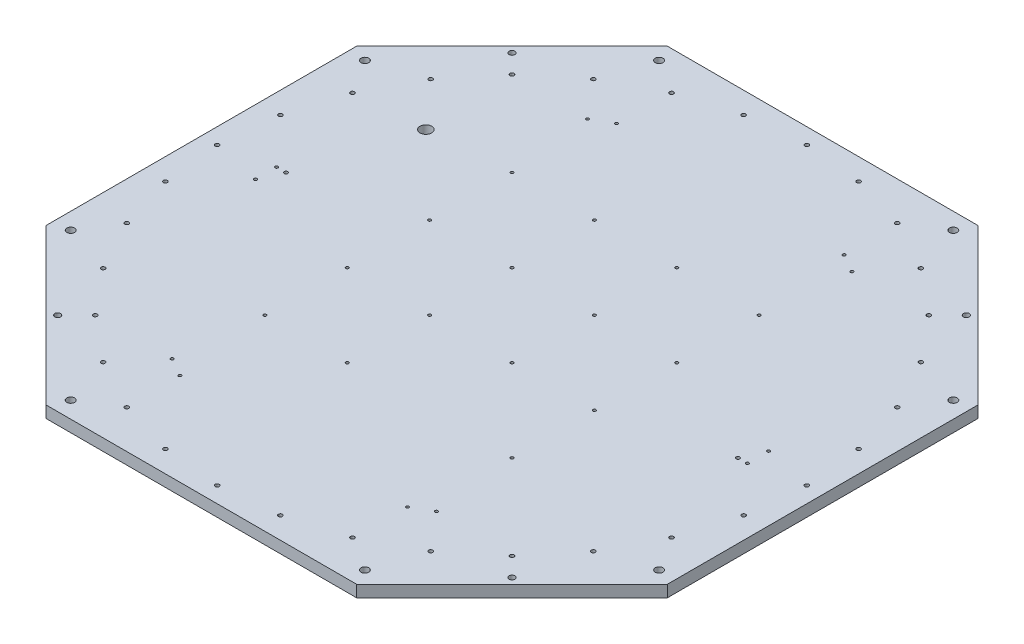
SolidWorks part; units mm, degrees
material "AISI 304"
ref_plane "Front" through (0, 0, 0) normal (0, 0, 1) x (1, 0, 0)
ref_plane "Top" through (0, 0, 0) normal (0, 1, 0) x (1, 0, 0)
ref_plane "Right" through (0, 0, 0) normal (1, 0, 0) x (0, 0, -1)
sketch "Sketch1" plane through (0, 0, 0) normal (0, 1, 0) x (1, 0, 0)
  line L0 (-131.9798, 264) -> (131.9798, 264)
  line L1 (131.9798, 264) -> (264, 131.9798)
  line L2 (264, 131.9798) -> (264, -131.9798)
  line L3 (264, 0) -> (0, 0) construction
  line L4 (0, 0) -> (0, 264) construction
  line L5 (131.9798, -264) -> (264, -131.9798)
  line L6 (-131.9798, -264) -> (131.9798, -264)
  line L7 (-131.9798, -264) -> (-264, -131.9798)
  line L8 (-264, 131.9798) -> (-264, -131.9798)
  line L9 (-131.9798, 264) -> (-264, 131.9798)
  point P12 (0, -264)
  point P21 (0, 0)
  dimension "D1" = 528
  dimension "D2" = 280
extrude "Boss-Extrude1" add sketch "Sketch1" along normal mid plane 10
hole_wizard "M3 Clearance Hole1" positions "Sketch2" profile "Sketch3" hole size "M3" standard "ANSI Metric" end condition up to next
sketch "Sketch2" plane through (0, 5, 0) normal (0, 1, 0) x (1, 0, 0)
  line L0 (-250.5, 0) -> (250.5, 0) construction
  point P0 (250.5, 0)
  point P6 (245.6867, -48.8701)
  point P7 (231.4318, -95.8622)
  point P8 (208.2831, -139.1703)
  point P9 (177.1302, -177.1302)
  point P10 (139.1703, -208.2831)
  point P11 (95.8622, -231.4318)
  point P12 (48.8701, -245.6867)
  point P13 (0, -250.5)
  point P14 (-48.8701, -245.6867)
  point P15 (-95.8622, -231.4318)
  point P16 (-139.1703, -208.2831)
  point P17 (-177.1302, -177.1302)
  point P18 (-208.2831, -139.1703)
  point P19 (-231.4318, -95.8622)
  point P20 (-245.6867, -48.8701)
  point P21 (-250.5, 0)
  point P22 (-245.6867, 48.8701)
  point P23 (-231.4318, 95.8622)
  point P24 (-208.2831, 139.1703)
  point P25 (-177.1302, 177.1302)
  point P26 (-139.1703, 208.2831)
  point P27 (-95.8622, 231.4318)
  point P28 (-48.8701, 245.6867)
  point P29 (0, 250.5)
  point P30 (48.8701, 245.6867)
  point P31 (95.8622, 231.4318)
  point P32 (139.1703, 208.2831)
  point P33 (177.1302, 177.1302)
  point P34 (208.2831, 139.1703)
  point P35 (231.4318, 95.8622)
  point P36 (245.6867, 48.8701)
  dimension "D2" = 501
  dimension "D1" = 32
sketch "Sketch3" plane through (250.5, 5, 0) normal (1, 0, 0) x (0, 0, 1)
  line L0 (0, 0) -> (0, 10)
  line L1 (0, 10) -> (1.7, 10)
  line L2 (1.7, 10) -> (1.7, 0)
  line L5 (1.7, 0) -> (0, 0)
  line L11 (0, -6.35) -> (0, 107.95) construction
  dimension "Thru Hole Dia." = 3.4
  dimension "Thru Hole Depth" = 10
hole_wizard "M3x0.5 Tapped Hole1" positions "Sketch10" profile "Sketch11" tap size "M3x0.5" standard "ANSI Metric"
sketch "Sketch10" plane through (0, 5, 0) normal (0, 1, 0) x (1, 0, 0)
  line L0 (209, 9) -> (209, 0) construction
  line L1 (209, 0) -> (209, -9) construction
  line L6 (0, 0) -> (209, 0) construction
  line L7 (-209, 9) -> (-209, -9) construction
  line L9 (-209, 0) -> (0, 0) construction
  point P0 (209, 9)
  point P2 (209, -9)
  point P39 (112.2942, -176.4993)
  point P40 (96.7058, -185.4993)
  point P41 (-96.7058, -185.4993)
  point P42 (-112.2942, -176.4993)
  point P43 (-209, -9)
  point P44 (-209, 9)
  point P45 (-112.2942, 176.4993)
  point P46 (-96.7058, 185.4993)
  point P47 (96.7058, 185.4993)
  point P48 (112.2942, 176.4993)
  dimension "D1" = 18
  dimension "D2" = 6
  dimension "D3" = 209
sketch "Sketch11" plane through (209, 5, -9) normal (1, 0, 0) x (0, 0, 1)
  line L0 (0, 0) -> (0, 8.2511)
  line L1 (0, 8.2511) -> (1.25, 7.5)
  line L2 (1.25, 7.5) -> (1.25, 0)
  line L5 (1.25, 0) -> (0, 0)
  line L10 (0, 8.2511) -> (-1.25, 7.5) construction
  line L11 (0, -6.35) -> (0, 107.95) construction
  dimension "Tap Drill Dia." = 2.5
  dimension "Tap Drill Depth" = 7.5
  dimension "Drill Angle" = 118
cosmetic thread "Hole Thread1" parameters "D1"=6, "D2"=3
cosmetic thread "Hole Thread2" parameters "D1"=6, "D2"=3
cosmetic thread "Hole Thread3" parameters "D1"=6, "D2"=3
cosmetic thread "Hole Thread4" parameters "D1"=6, "D2"=3
cosmetic thread "Hole Thread5" parameters "D1"=6, "D2"=3
cosmetic thread "Hole Thread6" parameters "D1"=6, "D2"=3
cosmetic thread "Hole Thread7" parameters "D1"=6, "D2"=3
cosmetic thread "Hole Thread8" parameters "D1"=6, "D2"=3
cosmetic thread "Hole Thread9" parameters "D1"=6, "D2"=3
cosmetic thread "Hole Thread10" parameters "D1"=6, "D2"=3
cosmetic thread "Hole Thread11" parameters "D1"=6, "D2"=3
cosmetic thread "Hole Thread12" parameters "D1"=6, "D2"=3
hole_wizard "Ø3.0mm Dowel Hole1" positions "Sketch12" profile "Sketch13" hole size "Ø3.0" standard "ANSI Metric"
sketch "Sketch12" plane through (0, 5, 0) normal (0, 1, 0) x (1, 0, 0)
  line L1 (201, -9) -> (209, -9) construction
  line L3 (-209, 9) -> (-201, 9) construction
  point P0 (201, -9)
  point P2 (-201, 9)
  dimension "D1" = 8
sketch "Sketch13" plane through (201, 5, 9) normal (1, 0, 0) x (0, 0, 1)
  line L0 (0, 0) -> (0, 6.9013)
  line L1 (0, 6.9013) -> (1.5, 6)
  line L2 (1.5, 6) -> (1.5, 0)
  line L5 (1.5, 0) -> (0, 0)
  line L10 (0, 6.9013) -> (-1.5, 6) construction
  line L11 (0, -6.35) -> (0, 107.95) construction
  dimension "Hole Dia." = 3
  dimension "Hole Depth" = 6
  dimension "Drill Angle" = 118
hole_wizard "M3x0.5 Tapped Hole2" positions "Sketch14" profile "Sketch15" tap size "M3x0.5" standard "ANSI Metric"
sketch "Sketch14" plane through (0, 5, 0) normal (0, 1, 0) x (1, 0, 0)
  line L11 (105, 105) -> (-105, -105) construction
  point P10 (-105, -105)
  point P84 (-35, -105)
  point P85 (35, -105) [skipped]
  point P86 (105, -105)
  point P87 (-35, -35)
  point P88 (35, -35)
  point P89 (105, -35)
  point P90 (-35, 35)
  point P91 (35, 35)
  point P92 (105, 35)
  point P93 (-35, 105)
  point P94 (35, 105)
  point P95 (105, 105)
  point P96 (-105, -35)
  point P97 (-105, 35)
  point P98 (-105, 105)
  dimension "D1" = 4
  dimension "D3" = 70
  dimension "D4" = 70
  dimension "D2" = 4
sketch "Sketch15" plane through (-105, 5, 105) normal (1, 0, 0) x (0, 0, 1)
  line L0 (0, 0) -> (0, 8.2511)
  line L1 (0, 8.2511) -> (1.25, 7.5)
  line L2 (1.25, 7.5) -> (1.25, 0)
  line L5 (1.25, 0) -> (0, 0)
  line L10 (0, 8.2511) -> (-1.25, 7.5) construction
  line L11 (0, -6.35) -> (0, 107.95) construction
  dimension "Tap Drill Dia." = 2.5
  dimension "Tap Drill Depth" = 7.5
  dimension "Drill Angle" = 118
cosmetic thread "Hole Thread13" parameters "D1"=6, "D2"=3
cosmetic thread "Hole Thread14" parameters "D1"=6, "D2"=3
cosmetic thread "Hole Thread15" parameters "D1"=6, "D2"=3
cosmetic thread "Hole Thread16" parameters "D1"=6, "D2"=3
cosmetic thread "Hole Thread17" parameters "D1"=6, "D2"=3
cosmetic thread "Hole Thread18" parameters "D1"=6, "D2"=3
cosmetic thread "Hole Thread19" parameters "D1"=6, "D2"=3
cosmetic thread "Hole Thread20" parameters "D1"=6, "D2"=3
cosmetic thread "Hole Thread21" parameters "D1"=6, "D2"=3
cosmetic thread "Hole Thread22" parameters "D1"=6, "D2"=3
cosmetic thread "Hole Thread23" parameters "D1"=6, "D2"=3
cosmetic thread "Hole Thread24" parameters "D1"=6, "D2"=3
cosmetic thread "Hole Thread25" parameters "D1"=6, "D2"=3
cosmetic thread "Hole Thread26" parameters "D1"=6, "D2"=3
cosmetic thread "Hole Thread27" parameters "D1"=6, "D2"=3
hole_wizard "M6x1.0 Tapped Hole1" positions "Sketch16" profile "Sketch17" tap size "M6x1.0" standard "ANSI Metric" end condition up to next
sketch "Sketch16" plane through (0, 5, 0) normal (0, 1, 0) x (1, 0, 0)
  line L0 (-193.0402, 193.0402) -> (-193.0402, -193.0402) construction
  line L1 (-193.0402, -193.0402) -> (193.0402, -193.0402) construction
  line L2 (193.0402, -193.0402) -> (193.0402, 193.0402) construction
  line L3 (193.0402, 193.0402) -> (-193.0402, 193.0402) construction
  line L5 (-193.0402, 193.0402) -> (193.0402, -193.0402) construction
  point P0 (-193.0402, -193.0402)
  point P6 (-193.0402, 193.0402)
  point P7 (193.0402, 193.0402)
  point P8 (193.0402, -193.0402)
  dimension "D2" = 546
  dimension "D1" = 4
sketch "Sketch17" plane through (-193.0402, 5, 193.0402) normal (1, 0, 0) x (0, 0, 1)
  line L0 (0, 0) -> (0, 10)
  line L1 (0, 10) -> (2.5, 10)
  line L2 (2.5, 10) -> (2.5, 0)
  line L5 (2.5, 0) -> (0, 0)
  line L11 (0, -6.35) -> (0, 107.95) construction
  dimension "Thru Tap Drill Dia." = 5
  dimension "Thru Tap Drill Depth" = 10
cosmetic thread "Hole Thread28" parameters "D2"=6
cosmetic thread "Hole Thread29" parameters "D2"=6
cosmetic thread "Hole Thread30" parameters "D2"=6
cosmetic thread "Hole Thread31" parameters "D2"=6
hole_wizard "M6 Clearance Hole1" positions "Sketch18" profile "Sketch19" hole size "M6" standard "ANSI Metric" end condition up to next
sketch "Sketch18" plane through (0, 5, 0) normal (0, 1, 0) x (1, 0, 0)
  line L0 (-264, 0) -> (0, 0) construction
  line L1 (-264, 131.9798) -> (-264, -131.9798) construction
  line L2 (0, 0) -> (0, -264) construction
  line L3 (-131.9798, -264) -> (131.9798, -264) construction
  line L5 (0, 0) -> (-197.9899, -197.9899) construction
  line L6 (-264, -131.9798) -> (-131.9798, -264) construction
  point P0 (-125, -250)
  point P22 (-250, -125)
  point P24 (-125, 250)
  point P25 (-250, 125)
  point P26 (125, -250)
  point P27 (250, -125)
  point P28 (250, 125)
  point P29 (125, 250)
  dimension "D1" = 250
  dimension "D2" = 500
sketch "Sketch19" plane through (-125, 5, 250) normal (1, 0, 0) x (0, 0, 1)
  line L0 (0, 0) -> (0, 10)
  line L1 (0, 10) -> (3.3, 10)
  line L2 (3.3, 10) -> (3.3, 0)
  line L5 (3.3, 0) -> (0, 0)
  line L11 (0, -6.35) -> (0, 107.95) construction
  dimension "Thru Hole Dia." = 6.6
  dimension "Thru Hole Depth" = 10
hole_wizard "7/16-20 Tapped Hole1" positions "Sketch25" profile "Sketch26" tap size "7/16-20" standard "ANSI Inch"
sketch "Sketch25" plane through (0, -5, 0) normal (0, -1, 0) x (-1, 0, 0)
  line L0 (0, 0) -> (251.0411, 144.9387) construction
  line L3 (0, 0) -> (-264, 0) construction
  line L4 (-264, -131.9798) -> (-264, 131.9798) construction
  line L7 (131.9798, 264) -> (264, 131.9798) construction
  point P0 (173.2051, 100)
  dimension "D1" = 30
  dimension "D2" = 200
sketch "Sketch26" plane through (-173.2051, -5, -100) normal (1, 0, 0) x (0, 0, -1)
  line L0 (0, 0) -> (0, 19.9806)
  line L1 (0, 19.9806) -> (4.9606, 17)
  line L2 (4.9606, 17) -> (4.9606, 0)
  line L5 (4.9606, 0) -> (0, 0)
  line L10 (0, 19.9806) -> (-4.9606, 17) construction
  line L11 (0, -6.35) -> (0, 107.95) construction
  dimension "Tap Drill Dia." = 9.9212
  dimension "Tap Drill Depth" = 17
  dimension "Drill Angle" = 118
cosmetic thread "Hole Thread32" parameters "D1"=10, "D2"=11.1125
sketch "Sketch28" plane through (0, 0, 0) normal (0, 1, 0) x (1, 0, 0)
  circle A0 centre (0, 0) radius 204.8 construction
